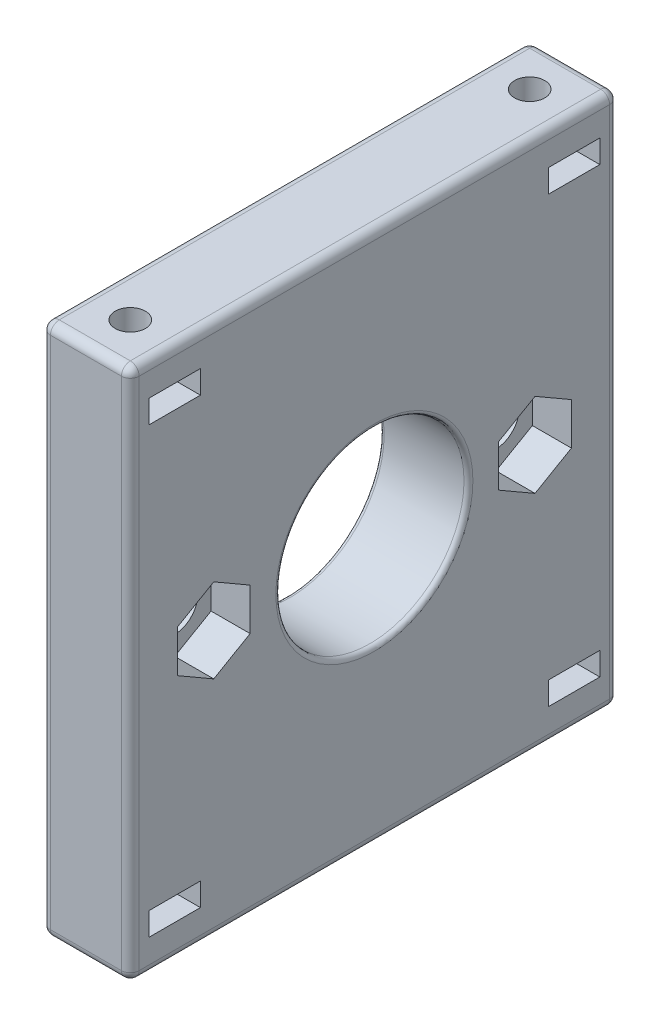
SolidWorks part; units mm, degrees
ref_plane "Front Plane" through (0, 0, 0) normal (0, 0, 1) x (1, 0, 0)
ref_plane "Top Plane" through (0, 0, 0) normal (0, 1, 0) x (1, 0, 0)
ref_plane "Right Plane" through (0, 0, 0) normal (1, 0, 0) x (0, 0, -1)
sketch "Sketch1" plane through (0, 0, 0) normal (1, 0, 0) x (0, 0, -1)
  line L1 (-27.5, 30) -> (27.5, 30)
  line L2 (-27.5, 30) -> (-27.5, -30)
  line L3 (-27.5, -30) -> (27.5, -30)
  line L4 (27.5, 30) -> (27.5, -30)
  line L5 (-27.5, 30) -> (27.5, -30) construction
  line L6 (-27.5, -30) -> (27.5, 30) construction
  point P0 (0, 0)
  dimension "D1" = 55
  dimension "D2" = 60
extrude "Boss-Extrude1" add sketch "Sketch1" along normal blind 10
sketch "Sketch2" plane through (0, -30, 0) normal (0, -1, 0) x (1, 0, 0)
  line L0 (5, 27.5) -> (5, -27.5) construction
  line L1 (10, 27.5) -> (0, 27.5) construction
  line L2 (10, -27.5) -> (0, -27.5) construction
  circle A0 centre (5, 22.5) radius 1.7
  circle A1 centre (5, -22.5) radius 1.7
  dimension "D1" = 3.4
  dimension "D2" = 3.4
  dimension "D3" = 5
  dimension "D4" = 5
extrude "Cut-Extrude1" cut sketch "Sketch2" against normal blind 10
sketch "Sketch3" plane through (0, 30, 0) normal (0, 1, 0) x (1, 0, 0)
  line L0 (5, 27.5) -> (5, -27.5) construction
  line L1 (10, 27.5) -> (0, 27.5) construction
  line L2 (10, -27.5) -> (0, -27.5) construction
  circle A0 centre (5, 22.5) radius 1.7
  circle A1 centre (5, -22.5) radius 1.7
  dimension "D1" = 5
  dimension "D2" = 3.4
  dimension "D3" = 5
  dimension "D4" = 3.4
extrude "Cut-Extrude2" cut sketch "Sketch3" against normal blind 10
sketch "Sketch4" plane through (10, 0, 0) normal (1, 0, 0) x (0, 0, -1)
  line L0 (0, 30) -> (0, -30) construction
  line L1 (27.5, 30) -> (-27.5, 30) construction
  line L2 (-27.5, -30) -> (27.5, -30) construction
  line L3 (27.5, 25) -> (-27.5, 25) construction
  line L4 (27.5, -30) -> (27.5, 30) construction
  line L5 (-27.5, 30) -> (-27.5, -30) construction
  line L6 (27.5, -25) -> (-27.5, -25) construction
  line L8 (-25.4, 26.3) -> (-19.6, 26.3)
  line L9 (-25.4, 26.3) -> (-25.4, 23.7)
  line L10 (-25.4, 23.7) -> (-19.6, 23.7)
  line L11 (-19.6, 26.3) -> (-19.6, 23.7)
  line L12 (-25.4, 26.3) -> (-19.6, 23.7) construction
  line L13 (-25.4, 23.7) -> (-19.6, 26.3) construction
  line L14 (19.6, 26.3) -> (25.4, 26.3)
  line L15 (19.6, 26.3) -> (19.6, 23.7)
  line L16 (19.6, 23.7) -> (25.4, 23.7)
  line L17 (25.4, 26.3) -> (25.4, 23.7)
  line L18 (19.6, 26.3) -> (25.4, 23.7) construction
  line L19 (19.6, 23.7) -> (25.4, 26.3) construction
  line L20 (-25.4, -23.7) -> (-19.6, -23.7)
  line L21 (-25.4, -23.7) -> (-25.4, -26.3)
  line L22 (-25.4, -26.3) -> (-19.6, -26.3)
  line L23 (-19.6, -23.7) -> (-19.6, -26.3)
  line L24 (-25.4, -23.7) -> (-19.6, -26.3) construction
  line L25 (-25.4, -26.3) -> (-19.6, -23.7) construction
  line L26 (19.6, -23.7) -> (25.4, -23.7)
  line L27 (19.6, -23.7) -> (19.6, -26.3)
  line L28 (19.6, -26.3) -> (25.4, -26.3)
  line L29 (25.4, -23.7) -> (25.4, -26.3)
  line L30 (19.6, -23.7) -> (25.4, -26.3) construction
  line L31 (19.6, -26.3) -> (25.4, -23.7) construction
  point P14 (-22.5, 25)
  point P19 (22.5, 25)
  point P24 (-22.5, -25)
  point P29 (22.5, -25)
  dimension "D1" = 2.6
  dimension "D2" = 2.6
  dimension "D3" = 2.6
  dimension "D4" = 2.6
  dimension "D5" = 5.8
  dimension "D6" = 5.8
  dimension "D7" = 5.8
  dimension "D8" = 5.8
  dimension "D9" = 5
  dimension "D10" = 5
  dimension "D11" = 5
  dimension "D12" = 5
  dimension "D13" = 5
  dimension "D14" = 5
extrude "Cut-Extrude3" cut sketch "Sketch4" against normal blind 9
sketch "Sketch5" plane through (0, 23.7, 0) normal (0, 1, 0) x (1, 0, 0)
  line L0 (1.8823, -22.5) -> (10, -22.5) construction
  line L1 (8.1177, -22.5) -> (6.5588, -19.8)
  line L2 (6.5588, -19.8) -> (3.4412, -19.8)
  line L3 (3.4412, -19.8) -> (1.8823, -22.5)
  line L4 (1.8823, -22.5) -> (3.4412, -25.2)
  line L5 (3.4412, -25.2) -> (6.5588, -25.2)
  line L6 (6.5588, -25.2) -> (8.1177, -22.5)
  line L7 (10, 27.5) -> (10, -27.5) construction
  circle A0 centre (5, -22.5) radius 2.7 construction
  dimension "D1" = 5.4
sketch "Sketch6" plane through (10, 0, 0) normal (1, 0, 0) x (0, 0, -1)
  line L0 (0, 30) -> (0, -30) construction
  line L1 (27.5, 30) -> (-27.5, 30) construction
  line L2 (-27.5, -30) -> (27.5, -30) construction
  line L3 (0, 0) -> (18.1, 0) construction
  line L4 (0, 0) -> (-18.1, 0) construction
  circle A0 centre (-18.1, 0) radius 2.6
  circle A1 centre (18.1, 0) radius 2.6
  circle A2 centre (0, 0) radius 10.6
  dimension "D3" = 5.2
  dimension "D4" = 5.2
  dimension "D5" = 21.2
  dimension "D1" = 18.1
  dimension "D2" = 18.1
extrude "Cut-Extrude4" cut sketch "Sketch6" against normal blind 15
fillet "Fillet1" radius 1 12 edges at (5, 30, -27.5) (0, 0, -27.5) (10, 0, -27.5) (5, -30, -27.5) (5, -30, 27.5) (10, -30, 0) (0, -30, 0) (0, 30, 0) (10, 30, 0) (5, 30, 27.5) (10, 0, 27.5) (0, 0, 27.5)
fillet "Fillet2" radius 0.5 6 edges at (0, 0, 15.5) (10, 0, 15.5) (10, 0, -10.6) (0, 0, -10.6) (10, 0, -20.7) (0, 0, -20.7)
sketch "Sketch7" plane through (10, 0, 0) normal (1, 0, 0) x (0, 0, -1)
  line L1 (-18.1, -4.7343) -> (-14, -2.3671)
  line L2 (-14, -2.3671) -> (-14, 2.3671)
  line L3 (-14, 2.3671) -> (-18.1, 4.7343)
  line L4 (-18.1, 4.7343) -> (-22.2, 2.3671)
  line L5 (-22.2, 2.3671) -> (-22.2, -2.3671)
  line L6 (-22.2, -2.3671) -> (-18.1, -4.7343)
  line L7 (18.1, -4.7343) -> (22.2, -2.3671)
  line L8 (22.2, -2.3671) -> (22.2, 2.3671)
  line L9 (22.2, 2.3671) -> (18.1, 4.7343)
  line L10 (18.1, 4.7343) -> (14, 2.3671)
  line L11 (14, 2.3671) -> (14, -2.3671)
  line L12 (14, -2.3671) -> (18.1, -4.7343)
  circle A0 centre (-18.1, 0) radius 4.1 construction
  circle A1 centre (18.1, 0) radius 4.1 construction
  dimension "D1" = 8.2
  dimension "D2" = 8.2
extrude "Cut-Extrude5" cut sketch "Sketch7" against normal blind 4.4
sketch "Sketch8" plane through (10, 0, 0) normal (1, 0, 0) x (0, 0, -1)
  line L0 (-22.5, 23.7) -> (-22.5, 30) construction
  line L1 (-19.8, 23.7) -> (-25.2, 23.7) construction
  line L2 (-26.5, 30) -> (26.5, 30) construction
  line L3 (-19.6, 25) -> (-27.5, 25) construction
  line L4 (-19.6, 23.7) -> (-19.6, 26.3) construction
  line L5 (-27.5, -29) -> (-27.5, 29) construction
  line L6 (-22.5, 30) -> (-22.5, 25)
  line L7 (-27.5, 25) -> (-22.5, 25)
